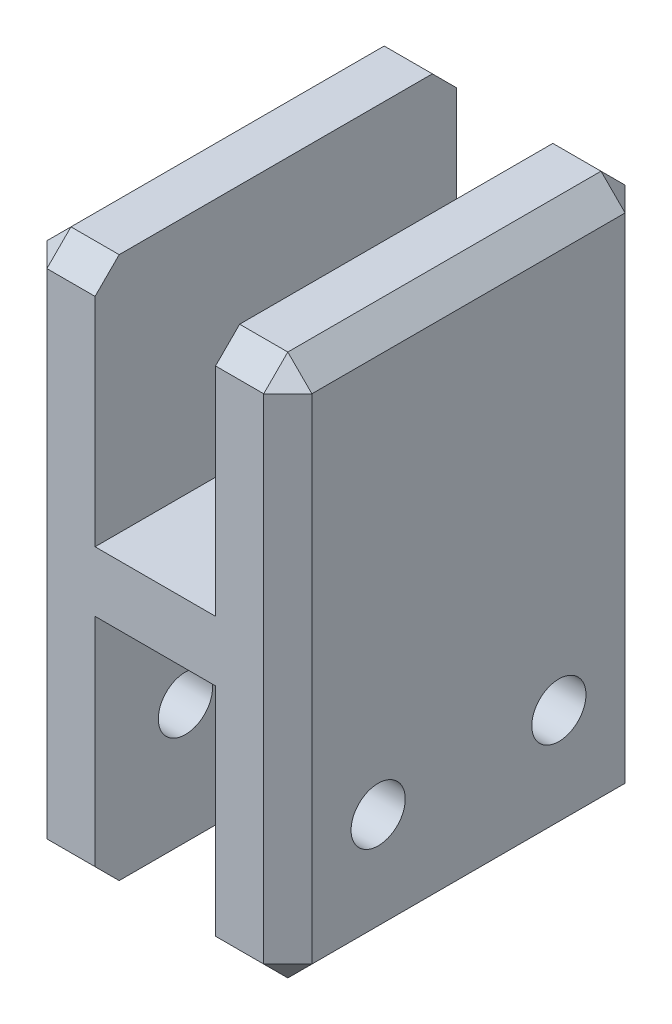
SolidWorks part; units mm, degrees
material "ABS"
ref_plane "Piano frontale" through (0, 0, 0) normal (0, 0, 1) x (1, 0, 0)
ref_plane "Piano superiore" through (0, 0, 0) normal (0, 1, 0) x (1, 0, 0)
ref_plane "Piano destro" through (0, 0, 0) normal (1, 0, 0) x (0, 0, -1)
sketch "Schizzo1" plane through (0, 0, 0) normal (0, 0, 1) x (1, 0, 0)
  line L0 (11, -25) -> (11, 20)
  line L1 (11, -25) -> (5, -25)
  line L2 (5, -25) -> (5, -5)
  line L3 (5, -5) -> (-5, -5)
  line L4 (-5, -5) -> (-5, -25)
  line L5 (-5, -25) -> (-11, -25)
  line L6 (-11, -25) -> (-11, 20)
  line L7 (11, 20) -> (5, 20)
  line L8 (5, 20) -> (5, 0)
  line L9 (5, 0) -> (-5, 0)
  line L10 (-5, 0) -> (-5, 20)
  line L11 (-5, 20) -> (-11, 20)
  dimension "D1" = 10
  dimension "D2" = 5
  dimension "D3" = 6
  dimension "D4" = 45
  dimension "D5" = 20
extrude "Estrusione-Estrusione1" add sketch "Schizzo1" along normal blind 30
hole_wizard "Foro lamato per Vite M4 a testa cilindrica piana-1" positions "Schizzo3D1" profile "Schizzo3" counterbore size "M4" standard "ISO"
sketch3d "Schizzo3D1"
  line L0 (-11, -25, 15) -> (-11, -15, 15) construction
  line L1 (-11, -25, 30) -> (-11, -25, 0) construction
  line L2 (-11, -15, 15) -> (-11, -15, 7.5) construction
  line L4 (-11, -15, 15) -> (-11, -15, 22.5) construction
  point P17 (-11, -15, 7.5)
  point P19 (-11, -15, 22.5)
  dimension "D1" = 10
  dimension "D2" = 15
sketch "Schizzo3" plane through (-11, -15, 22.5) normal (0, 1, 0) x (0, 0, 1)
  line L0 (0, 0) -> (0, 31.3519)
  line L1 (0, 31.3519) -> (2.25, 30)
  line L2 (2.25, 30) -> (2.25, 2.6)
  line L3 (2.25, 2.6) -> (5, 2.6)
  line L4 (5, 2.6) -> (5, 0)
  line L5 (5, 0) -> (0, 0)
  line L10 (0, 31.3519) -> (-2.25, 30) construction
  line L11 (0, -6.35) -> (0, 107.95) construction
  dimension "Hole Dia." = 4.5
  dimension "Hole Depth" = 30
  dimension "C'Bore Dia." = 10
  dimension "C'Bore Depth" = 2.6
  dimension "Drill Angle" = 118
chamfer "Smusso1" distance 2 angle 45 16 edges at (8, -25, 0) (8, -25, 30) (11, -25, 15) (11, -2.5, 0) (11, -2.5, 30) (8, 20, 0) (11, 20, 15) (8, 20, 30) (-8, -25, 0) (-8, -25, 30) (-8, 20, 0) (-8, 20, 30) (-11, 20, 15) (-11, -2.5, 30) (-11, -2.5, 0) (-11, -25, 15)
